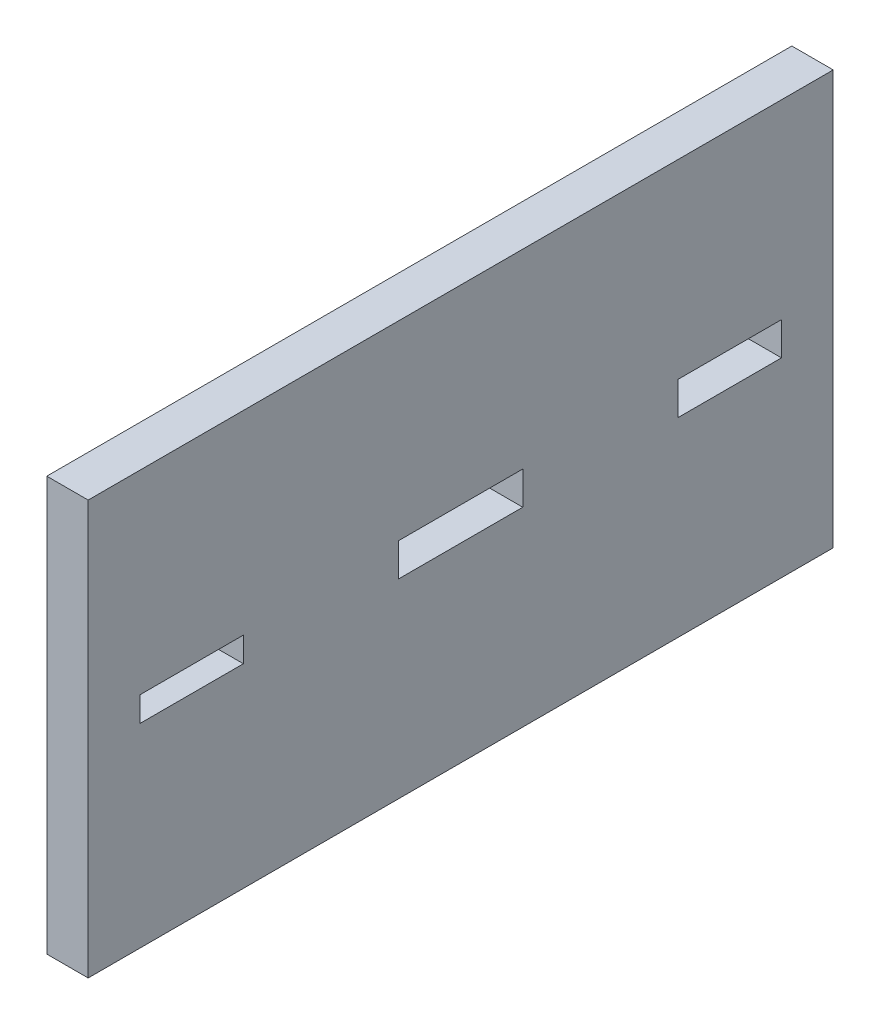
SolidWorks part; units mm, degrees
ref_plane "Front Plane" through (0, 0, 0) normal (0, 0, 1) x (1, 0, 0)
ref_plane "Top Plane" through (0, 0, 0) normal (0, 1, 0) x (1, 0, 0)
ref_plane "Right Plane" through (0, 0, 0) normal (1, 0, 0) x (0, 0, -1)
sketch "Sketch1" plane through (0, 0, 0) normal (1, 0, 0) x (0, 0, -1)
  line L0 (0, 0) -> (-65, 0) construction
  line L1 (-90, 50) -> (90, 50)
  line L2 (-90, 50) -> (-90, -50)
  line L3 (-90, -50) -> (90, -50)
  line L4 (90, 50) -> (90, -50)
  line L5 (-15, 4) -> (15, 4)
  line L6 (-15, 4) -> (-15, -4)
  line L7 (-15, -4) -> (15, -4)
  line L8 (15, 4) -> (15, -4)
  line L9 (0, 0) -> (65, 0) construction
  line L11 (-77.5, 3) -> (-52.5, 3)
  line L12 (-77.5, 3) -> (-77.5, -3)
  line L13 (-77.5, -3) -> (-52.5, -3)
  line L14 (-52.5, 3) -> (-52.5, -3)
  line L15 (52.5, 4) -> (77.5, 4)
  line L16 (52.5, 4) -> (52.5, -4)
  line L17 (52.5, -4) -> (77.5, -4)
  line L18 (77.5, 4) -> (77.5, -4)
  point P4 (0, 50)
  point P6 (90, 0)
  point P11 (0, 4)
  point P12 (15, 0)
  point P20 (-65, 3)
  point P21 (-52.5, 0)
  point P26 (77.5, 0)
  point P27 (65, 4)
  dimension "D1" = 100
  dimension "D2" = 180
  dimension "D3" = 8
  dimension "D4" = 30
  dimension "D5" = 65
  dimension "D6" = 8
  dimension "D7" = 6
  dimension "D8" = 25
  dimension "D9" = 25
extrude "Boss-Extrude1" add sketch "Sketch1" along normal blind 10
